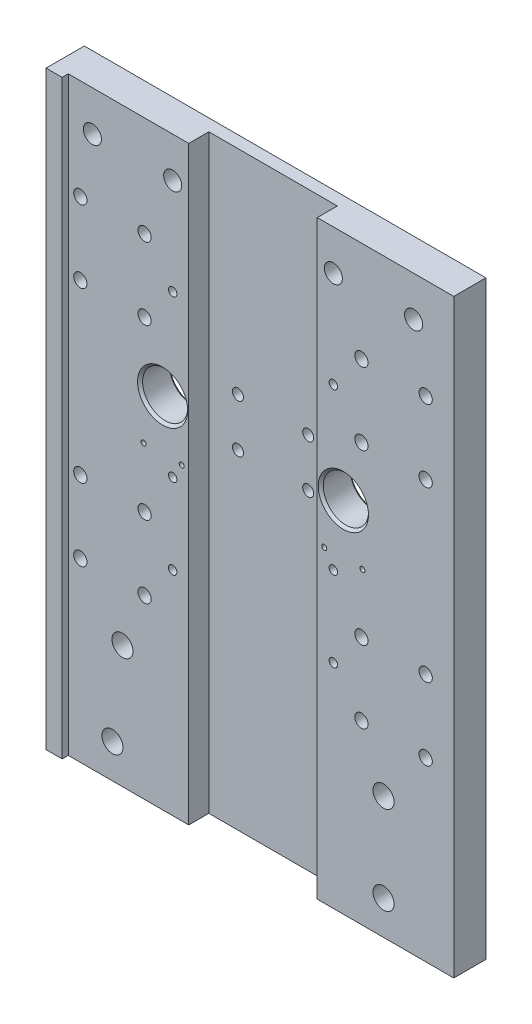
SolidWorks part; units mm, degrees
material "6061-T6 (SS)"
ref_plane "Front Plane" through (0, 0, 0) normal (0, 0, 1) x (1, 0, 0)
ref_plane "Top Plane" through (0, 0, 0) normal (0, 1, 0) x (1, 0, 0)
ref_plane "Right Plane" through (0, 0, 0) normal (1, 0, 0) x (0, 0, -1)
sketch "Sketch1" plane through (0, 0, 0) normal (0, 0, 1) x (1, 0, 0)
  line L0 (0, -161.7) -> (0, 161.7) construction
  line L1 (-70, 60) -> (70, 60) construction
  line L2 (-70, 60) -> (-70, -60) construction
  line L3 (-70, -60) -> (70, -60) construction
  line L4 (70, 60) -> (70, -60) construction
  line L5 (-70, 60) -> (70, -60) construction
  line L6 (-70, -60) -> (70, 60) construction
  line L7 (-86, 78) -> (-54, 78) construction
  line L8 (-86, 78) -> (-86, 42) construction
  line L9 (-86, 42) -> (-54, 42) construction
  line L10 (-54, 78) -> (-54, 42) construction
  line L11 (-86, 78) -> (-54, 42) construction
  line L12 (-86, 42) -> (-54, 78) construction
  line L13 (-100, 128) -> (100, 128)
  line L14 (-100, 128) -> (-100, -166)
  line L15 (-100, -166) -> (100, -166)
  line L16 (100, 128) -> (100, -166)
  line L17 (-100, -88) -> (100, -88) construction
  line L18 (-100, 88) -> (100, 88) construction
  line L19 (54, -42) -> (86, -42) construction
  line L20 (54, -42) -> (54, -78) construction
  line L21 (54, -78) -> (86, -78) construction
  line L22 (86, -42) -> (86, -78) construction
  line L23 (54, -42) -> (86, -78) construction
  line L24 (54, -78) -> (86, -42) construction
  line L25 (35.5, -12.5) -> (54.5, -12.5) construction
  line L26 (-17.5, 22) -> (17.5, 22) construction
  line L27 (-17.5, 22) -> (-17.5, -2) construction
  line L28 (-17.5, -2) -> (17.5, -2) construction
  line L29 (17.5, 22) -> (17.5, -2) construction
  line L30 (-17.5, 22) -> (17.5, -2) construction
  line L31 (-17.5, -2) -> (17.5, 22) construction
  line L32 (-100, -88) -> (100, -166) construction
  point P0 (0, 0)
  point P14 (0, -166)
  point P23 (0, 10)
  point P33 (0, -127)
  point P35 (45, -12.5)
  dimension "D1" = 120
  dimension "D2" = 140
  dimension "D3" = 36
  dimension "D4" = 32
  dimension "D5" = 78
  dimension "D6" = 10
  dimension "D7" = 40
  dimension "D8" = 10
  dimension "D9" = 200
  dimension "D10" = 24
  dimension "D11" = 35
  dimension "D12" = 10
  dimension "D13" = 19
  dimension "D14" = 45
  dimension "D15" = 47.5
extrude "Boss-Extrude1" add sketch "Sketch1" along normal blind 19.05
sketch "Sketch2" plane through (0, 0, 19.05) normal (0, 0, 1) x (1, 0, 0)
  line L0 (100, 128) -> (-100, 128) construction
  line L1 (-92, 128) -> (100, 128)
  line L2 (-92, 128) -> (-92, -166)
  line L3 (-92, -166) -> (100, -166)
  line L4 (100, 128) -> (100, -166)
  line L7 (-70, 60) -> (-70, -60) construction
  dimension "D1" = 22
extrude "Cut-Extrude1" cut sketch "Sketch2" against normal offset from surface (3.05 mm away) 16 up to face at (0, -19, 0)
sketch "Sketch3" plane through (0, 0, 16) normal (0, 0, 1) x (1, 0, 0)
  line L0 (-100, 128) -> (100, 128) construction
  line L1 (-32, 128) -> (32, 128)
  line L2 (-32, 128) -> (-32, -166)
  line L3 (-32, -166) -> (32, -166)
  line L4 (32, 128) -> (32, -166)
  line L5 (-100, -166) -> (100, -166) construction
  line L6 (0, -161.7) -> (0, 161.7) construction
  point P8 (0, -166)
  dimension "D1" = 64
extrude "Cut-Extrude2" cut sketch "Sketch3" against normal blind 10
hole_wizard "M6 Clearance Hole1" positions "Sketch4" profile "Sketch5" hole size "M6" standard "ANSI Metric" end condition up to next
sketch "Sketch4" plane through (0, 0, 16) normal (0, 0, 1) x (1, 0, 0)
  point P0 (54, -42)
  point P3 (86, -42)
  point P6 (86, -78)
  point P9 (54, -78)
sketch "Sketch5" plane through (54, -42, 16) normal (1, 0, 0) x (0, -1, 0)
  line L0 (0, 0) -> (0, 16)
  line L1 (0, 16) -> (3.3, 16)
  line L2 (3.3, 16) -> (3.3, 0)
  line L5 (3.3, 0) -> (0, 0)
  line L11 (0, -6.35) -> (0, 107.95) construction
  dimension "Thru Hole Dia." = 6.6
  dimension "Thru Hole Depth" = 16
mirror "Mirror1" about plane through (0, 0, 0) normal (0, 1, 0) of "M6 Clearance Hole1"
hole_wizard "M3x0.5 Tapped Hole1" positions "Sketch6" profile "Sketch8" tap size "M3x0.5" standard "ANSI Metric"
sketch "Sketch6" plane through (0, 0, 16) normal (0, 0, 1) x (1, 0, 0)
  point P0 (54.5, -12.5)
  point P3 (35.5, -12.5)
sketch "Sketch8" plane through (54.5, -12.5, 16) normal (1, 0, 0) x (0, -1, 0)
  line L0 (0, 0) -> (0, 8.2511)
  line L1 (0, 8.2511) -> (1.25, 7.5)
  line L2 (1.25, 7.5) -> (1.25, 0)
  line L5 (1.25, 0) -> (0, 0)
  line L10 (0, 8.2511) -> (-1.25, 7.5) construction
  line L11 (0, -6.35) -> (0, 107.95) construction
  dimension "Tap Drill Dia." = 2.5
  dimension "Tap Drill Depth" = 7.5
  dimension "Drill Angle" = 118
cosmetic thread "Hole Thread1" parameters "D1"=6, "D2"=3
cosmetic thread "Hole Thread2" parameters "D1"=6, "D2"=3
hole_wizard "Ø22.5 (22.5) Diameter Hole1" positions "Sketch9" profile "Sketch10" hole size "Ø22.5" standard "ANSI Metric" end condition up to next
sketch "Sketch9" plane through (0, 0, 16) normal (0, 0, 1) x (1, 0, 0)
  line L0 (45, -12.5) -> (45, 12.5)
  line L1 (35.5, -12.5) -> (54.5, -12.5) construction
  point P0 (45, 12.5)
  dimension "D1" = 25
sketch "Sketch10" plane through (45, 12.5, 16) normal (1, 0, 0) x (0, -1, 0)
  line L0 (0, 0) -> (0, 16)
  line L1 (0, 16) -> (12.5, 16)
  line L2 (11.25, 14.75) -> (11.25, 1.25)
  line L3 (11.25, 1.25) -> (12.5, 0)
  line L5 (12.5, 0) -> (0, 0)
  line L6 (-11.25, 1.25) -> (-12.5, 0) construction
  line L7 (12.5, 16) -> (11.25, 14.75)
  line L8 (-12.5, 16) -> (-11.25, 14.75) construction
  line L11 (0, -6.35) -> (0, 107.95) construction
  dimension "Thru Hole Dia." = 22.5
  dimension "Thru Hole Depth" = 16
  dimension "Near C'Sink Dia." = 25
  dimension "Near C'Sink Angle" = 90
  dimension "Far C'Sink Dia." = 25
  dimension "Far C'Sink Angle" = 90
hole_wizard "M8 Clearance Hole1" positions "Sketch13" profile "Sketch14" hole size "M8" standard "ANSI Metric" end condition up to next
sketch "Sketch13" plane through (0, 0, 16) normal (0, 0, 1) x (1, 0, 0)
  line L0 (40, 108) -> (80, 108)
  line L2 (-100, 88) -> (100, 88) construction
  line L3 (0, -161.7) -> (0, 161.7) construction
  point P1 (40, 108)
  point P2 (80, 108)
  dimension "D1" = 20
  dimension "D2" = 40
  dimension "D3" = 40
sketch "Sketch14" plane through (40, 108, 16) normal (1, 0, 0) x (0, -1, 0)
  line L0 (0, 0) -> (0, 16)
  line L1 (0, 16) -> (4.5, 16)
  line L2 (4.5, 16) -> (4.5, 0)
  line L5 (4.5, 0) -> (0, 0)
  line L11 (0, -6.35) -> (0, 107.95) construction
  dimension "Thru Hole Dia." = 9
  dimension "Thru Hole Depth" = 16
hole_wizard "M5x0.8 Tapped Hole1" positions "Sketch15" profile "Sketch16" tap size "M5x0.8" standard "ANSI Metric" end condition up to next
sketch "Sketch15" plane through (0, 0, 16) normal (0, 0, 1) x (1, 0, 0)
  line L0 (40, 60) -> (40, -20)
  line L1 (40, -20) -> (40, -60)
  line L3 (-70, -60) -> (70, -60) construction
  line L4 (-70, 60) -> (70, 60) construction
  point P0 (40, 60)
  point P1 (40, -20)
  point P3 (40, -60)
  dimension "D1" = 40
  dimension "D2" = 80
  dimension "D3" = 40
sketch "Sketch16" plane through (40, 60, 16) normal (1, 0, 0) x (0, -1, 0)
  line L0 (0, 0) -> (0, 16)
  line L1 (0, 16) -> (2.1, 16)
  line L2 (2.1, 16) -> (2.1, 0)
  line L5 (2.1, 0) -> (0, 0)
  line L11 (0, -6.35) -> (0, 107.95) construction
  dimension "Thru Tap Drill Dia." = 4.2
  dimension "Thru Tap Drill Depth" = 16
cosmetic thread "Hole Thread5"
cosmetic thread "Hole Thread6"
cosmetic thread "Hole Thread7"
mirror "Mirror2" about plane through (0, 0, 0) normal (1, 0, 0) of "M5x0.8 Tapped Hole1", "M8 Clearance Hole1", "Mirror1", "M3x0.5 Tapped Hole1", "Ø22.5 (22.5) Diameter Hole1", "M6 Clearance Hole1"
cosmetic thread "Hole Thread3"
cosmetic thread "Hole Thread4"
cosmetic thread "Hole Thread8"
cosmetic thread "Hole Thread9"
cosmetic thread "Hole Thread10"
hole_wizard "M5 Clearance Hole1" positions "Sketch11" profile "Sketch12" hole size "M5" standard "ANSI Metric" end condition up to next
sketch "Sketch11" plane through (0, 0, 6) normal (0, 0, 1) x (1, 0, 0)
  point P0 (-17.5, 22)
  point P3 (17.5, 22)
  point P6 (17.5, -2)
  point P9 (-17.5, -2)
sketch "Sketch12" plane through (-17.5, 22, 6) normal (1, 0, 0) x (0, -1, 0)
  line L0 (0, 0) -> (0, 6)
  line L1 (0, 6) -> (2.75, 6)
  line L2 (2.75, 6) -> (2.75, 0)
  line L5 (2.75, 0) -> (0, 0)
  line L11 (0, -6.35) -> (0, 107.95) construction
  dimension "Thru Hole Dia." = 5.5
  dimension "Thru Hole Depth" = 6
hole_wizard "M12x1.5 Tapped Hole1" positions "Sketch17" profile "Sketch18" tap size "M12x1.5" standard "ANSI Metric" end condition up to next
sketch "Sketch17" plane through (0, 0, 16) normal (0, 0, 1) x (1, 0, 0)
  line L1 (-65, -105) -> (65, -105)
  line L2 (-65, -105) -> (-65, -149)
  line L3 (-65, -149) -> (65, -149)
  line L4 (65, -105) -> (65, -149)
  line L5 (-65, -105) -> (65, -149) construction
  line L6 (-65, -149) -> (65, -105) construction
  line L7 (-65, -149) -> (-70, -149)
  point P2 (65, -149)
  point P63 (-65, -105)
  point P65 (65, -105)
  point P72 (-70, -149)
  dimension "D1" = 44
  dimension "D2" = 130
  dimension "D3" = 5
sketch "Sketch18" plane through (65, -149, 16) normal (1, 0, 0) x (0, -1, 0)
  line L0 (0, 0) -> (0, 16)
  line L1 (0, 16) -> (5.25, 16)
  line L2 (5.25, 16) -> (5.25, 0)
  line L5 (5.25, 0) -> (0, 0)
  line L11 (0, -6.35) -> (0, 107.95) construction
  dimension "Thru Tap Drill Dia." = 10.5
  dimension "Thru Tap Drill Depth" = 16
cosmetic thread "Hole Thread11"
cosmetic thread "Hole Thread12"
cosmetic thread "Hole Thread13"
cosmetic thread "Hole Thread14"
